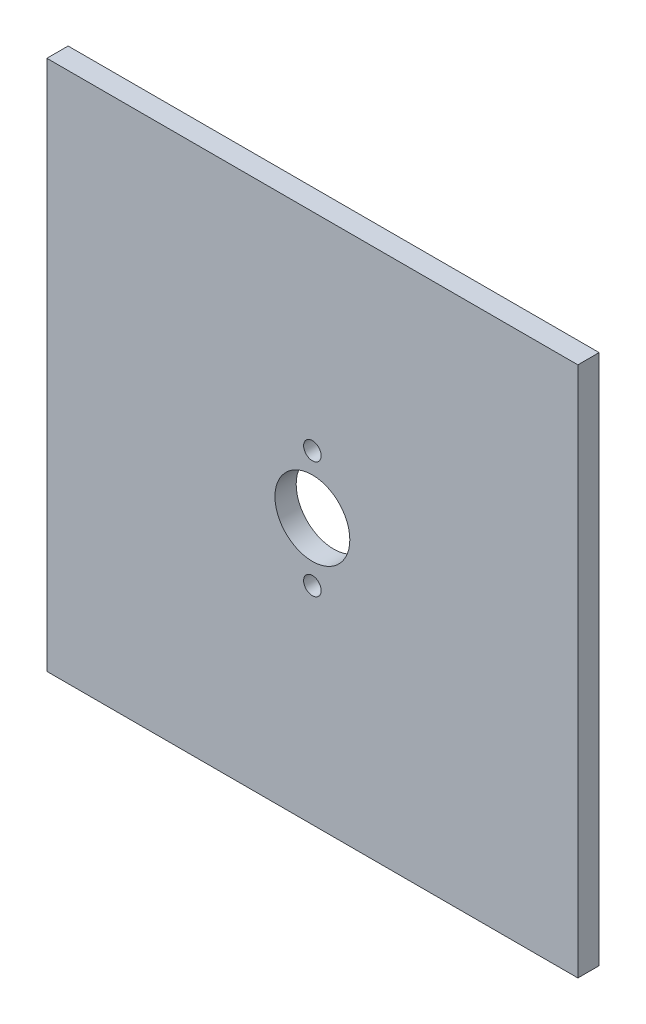
SolidWorks part; units mm, degrees
ref_plane "Front Plane" through (0, 0, 0) normal (0, 0, 1) x (1, 0, 0)
ref_plane "Top Plane" through (0, 0, 0) normal (0, 1, 0) x (1, 0, 0)
ref_plane "Right Plane" through (0, 0, 0) normal (1, 0, 0) x (0, 0, -1)
sketch "Sketch4" plane through (0, 0, 0) normal (0, 0, 1) x (1, 0, 0)
  line L1 (0, 0) -> (-50, 0)
  line L2 (0, 0) -> (0, 50)
  line L3 (0, 50) -> (-50, 50)
  line L4 (-50, 0) -> (-50, 50)
  dimension "D1" = 50
  dimension "D2" = 50
extrude "Boss-Extrude2" add sketch "Sketch4" along normal blind 2
sketch "Sketch5" plane through (0, 0, 2) normal (0, 0, 1) x (1, 0, 0)
  line L0 (-25, 50) -> (-25, 0) construction
  line L1 (0, 50) -> (-50, 50) construction
  line L2 (-50, 0) -> (0, 0) construction
  line L3 (-50, 25) -> (0, 25) construction
  line L4 (-50, 50) -> (-50, 0) construction
  line L5 (0, 0) -> (0, 50) construction
  circle A0 centre (-25, 30.5) radius 0.825
  circle A1 centre (-25, 19.5) radius 0.825
  dimension "D1" = 1.65
  dimension "D2" = 1.65
  dimension "D3" = 11
  dimension "D4" = 5.5
extrude "Cut-Extrude1" cut sketch "Sketch5" against normal up to next
sketch "Sketch6" plane through (0, 0, 0) normal (0, 0, -1) x (-1, 0, 0)
  line L0 (25, 50) -> (25, 0) construction
  line L1 (0, 50) -> (50, 50) construction
  line L2 (50, 0) -> (0, 0) construction
  line L3 (0, 25) -> (50, 25) construction
  line L4 (0, 0) -> (0, 50) construction
  line L5 (50, 50) -> (50, 0) construction
  circle A0 centre (25, 25) radius 3.525
  dimension "D1" = 7.05
extrude "Cut-Extrude2" cut sketch "Sketch6" against normal up to next
